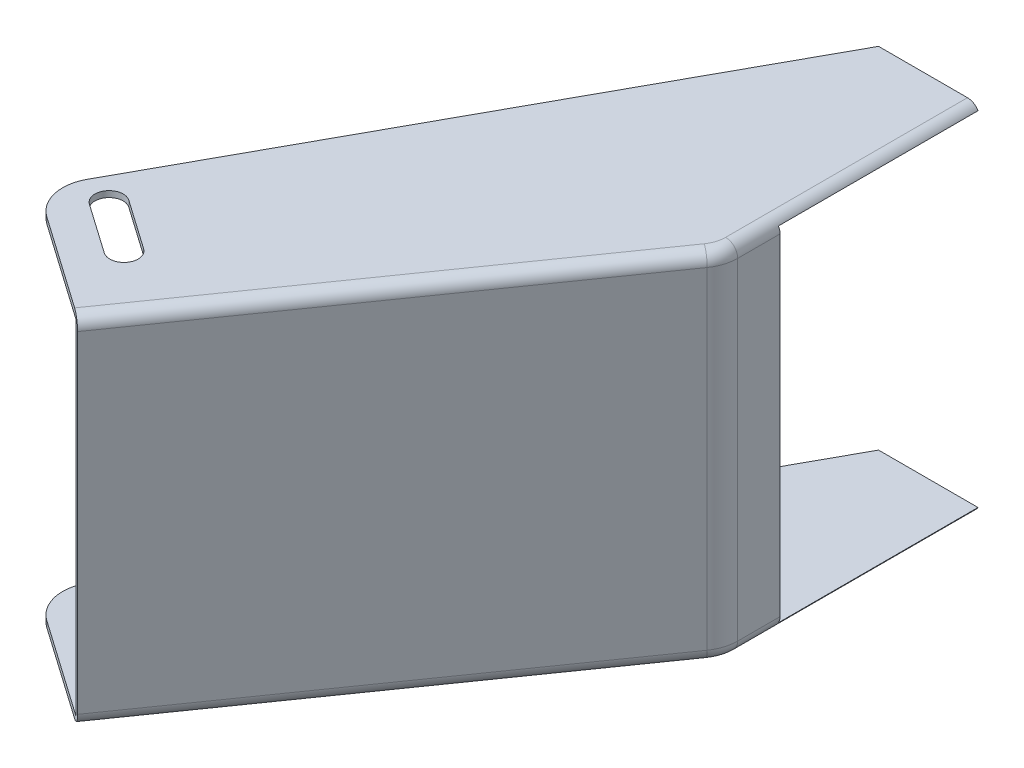
SolidWorks part; units mm, degrees
ref_plane "Front Plane" through (0, 0, 0) normal (0, 0, 1) x (1, 0, 0)
ref_plane "Top Plane" through (0, 0, 0) normal (0, 1, 0) x (1, 0, 0)
ref_plane "Right Plane" through (0, 0, 0) normal (1, 0, 0) x (0, 0, -1)
sketch "Sketch1" plane through (0, 0, 0) normal (0, 1, 0) x (1, 0, 0)
  line L0 (0, 0) -> (0, -63)
  line L1 (0, -63) -> (-65.9613, -157.2025)
  line L2 (-1.5, 0) -> (-1.5, -62.5271)
  line L3 (-1.5, -62.5271) -> (-67.19, -156.3421)
  line L4 (-1.5, 0) -> (0, 0)
  line L5 (-67.19, -156.3421) -> (-65.9613, -157.2025)
  dimension "D1" = 63
  dimension "D2" = 115
  dimension "D3" = 145
  dimension "D4" = 1.5
extrude "Boss-Extrude1" add sketch "Sketch1" along normal blind 87.5
sketch "Sketch2" plane through (0, 0, 0) normal (0, -1, 0) x (1, 0, 0)
  line L0 (0, 0) -> (-25, 0)
  line L1 (-25, 0) -> (-94.4106, 126.3985)
  line L2 (-91.381, 139.4034) -> (-65.9613, 157.2025)
  line L3 (-65.9613, 157.2025) -> (0, 63)
  line L4 (0, 63) -> (0, 0)
  line L5 (-74.5195, 137.1711) -> (-86.8068, 128.5674) construction
  line L6 (-72.512, 134.304) -> (-84.7992, 125.7004)
  line L7 (-76.527, 140.0381) -> (-88.8143, 131.4345)
  arc A0 (-72.512, 134.304) -> (-76.527, 140.0381) centre (-74.5195, 137.1711) ccw
  arc A1 (-88.8143, 131.4345) -> (-84.7992, 125.7004) centre (-86.8068, 128.5674) ccw
  arc A2 (-94.4106, 126.3985) -> (-91.381, 139.4034) centre (-85.6453, 131.2119) cw
  point P10 (-80.6631, 132.8692)
  point P15 (-71.6524, 139.1786)
  point P18 (-98.7274, 134.2594)
  dimension "D7" = 10
  dimension "D1" = 25
  dimension "D2" = 40
  dimension "D3" = 15
  dimension "D4" = 7
  dimension "D5" = 15
  dimension "D6" = 8
extrude "Boss-Extrude2" add sketch "Sketch2" against normal blind 1.5
ref_plane "Plane1" through (0, 44, 0) normal (0, 1, 0) x (1, 0, 0)
mirror "Mirror1" about plane through (0, 44, 0) normal (0, 1, 0) of "Boss-Extrude2"
fillet "Fillet1" radius 10 2 edges at (0, 44, 63) (-1.5, 44, 62.5271)
fillet "Fillet2" radius 3 6 edges at (-33.8849, 0, 111.3926) (-0.4628, 0, 62.8541) (0, 0, 29.9235) (-33.8849, 88, 111.3926) (-0.4628, 88, 62.8541) (0, 88, 29.9235)
sketch "Sketch3" plane through (-1.5, 0, 0) normal (-1, 0, 0) x (0, 0, 1)
  line L0 (0, 1.5) -> (59.3741, 1.5) construction
  line L1 (0, 86.5) -> (49.3741, 86.5)
  line L2 (0, 86.5) -> (0, 1.5)
  line L3 (0, 1.5) -> (49.3741, 1.5)
  line L4 (49.3741, 86.5) -> (49.3741, 1.5)
  line L5 (59.3741, 1.5) -> (59.3741, 86.5) construction
  dimension "D1" = 10
extrude "Cut-Extrude1" cut sketch "Sketch3" against normal up to surface (1.5 mm away) up to face at (0, 44, 29.9235)
